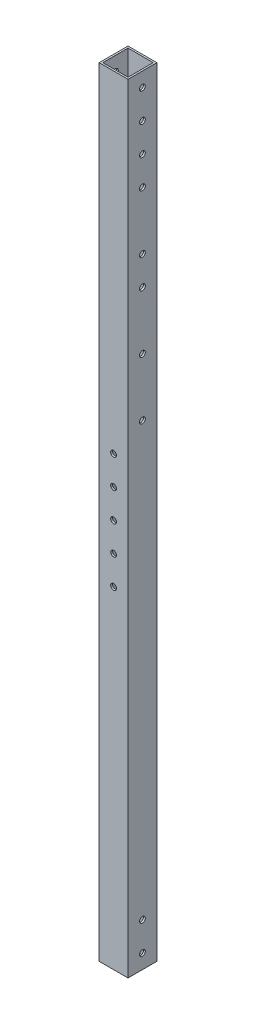
SolidWorks part; units mm, degrees
material "6061-T6 (SS)"
ref_plane "Front Plane" through (0, 0, 0) normal (0, 0, 1) x (1, 0, 0)
ref_plane "Top Plane" through (0, 0, 0) normal (0, 1, 0) x (1, 0, 0)
ref_plane "Right Plane" through (0, 0, 0) normal (1, 0, 0) x (0, 0, -1)
sketch "Sketch1" plane through (0, 0, 0) normal (0, 1, 0) x (1, 0, 0)
  line L1 (-12.7, -12.7) -> (12.7, -12.7)
  line L2 (-12.7, -12.7) -> (-12.7, 12.7)
  line L3 (-12.7, 12.7) -> (12.7, 12.7)
  line L4 (12.7, -12.7) -> (12.7, 12.7)
  line L5 (-12.7, -12.7) -> (12.7, 12.7) construction
  line L6 (-12.7, 12.7) -> (12.7, -12.7) construction
  line L7 (-11.1125, -11.1125) -> (11.1125, -11.1125)
  line L8 (-11.1125, -11.1125) -> (-11.1125, 11.1125)
  line L9 (-11.1125, 11.1125) -> (11.1125, 11.1125)
  line L10 (11.1125, -11.1125) -> (11.1125, 11.1125)
  line L11 (-11.1125, -11.1125) -> (11.1125, 11.1125) construction
  line L12 (-11.1125, 11.1125) -> (11.1125, -11.1125) construction
  point P0 (0, 0)
  point P6 (0, 0)
  dimension "D1" = 25.4
  dimension "D2" = 1.5875
extrude "Boss-Extrude1" add sketch "Sketch1" along normal blind 685.8
hole_wizard "#7 (0.201) Diameter Hole1" positions "Sketch2" profile "Sketch3" hole size "#7" standard "ANSI Inch"
sketch "Sketch2" plane through (0, 0, 12.7) normal (0, 0, 1) x (1, 0, 0)
  point P21 (0, 292.1)
  point P22 (0, 317.5)
  point P23 (0, 342.9)
  point P24 (0, 368.3)
  point P25 (0, 393.7)
  point P38 (0, 673.1)
  point P39 (0, 647.7)
  point P40 (0, 622.3)
  point P41 (0, 596.9)
  point P42 (0, 571.5)
  point P43 (0, 546.1)
  point P44 (0, 520.7)
  point P45 (0, 495.3)
  point P46 (0, 469.9)
  point P47 (0, 444.5)
  point P48 (0, 419.1)
  point P49 (0, 241.3)
  point P50 (0, 215.9)
  point P51 (0, 190.5)
  point P52 (0, 165.1)
  point P53 (0, 139.7)
  point P54 (0, 114.3)
  point P55 (0, 88.9)
  point P56 (0, 63.5)
  point P57 (0, 38.1)
  dimension "D1" = 292.1
  dimension "D3" = 25.4
  dimension "D2" = 25.4
  dimension "D4" = 25.4
  dimension "D5" = 25.4
sketch "Sketch3" plane through (0, 292.1, 12.7) normal (1, 0, 0) x (0, -1, 0)
  line L0 (0, 0) -> (0, 25.4)
  line L1 (0, 25.4) -> (2.5527, 25.4)
  line L2 (2.5527, 25.4) -> (2.5527, 0)
  line L5 (2.5527, 0) -> (0, 0)
  line L11 (0, -6.35) -> (0, 107.95) construction
  dimension "Thru Hole Dia." = 5.1054
  dimension "Thru Hole Depth" = 25.4
hole_wizard "#7 (0.201) Diameter Hole2" positions "Sketch4" profile "Sketch5" hole size "#7" standard "ANSI Inch"
sketch "Sketch4" plane through (12.7, 0, 0) normal (1, 0, 0) x (0, 0, -1)
  line L0 (-12.7, 0) -> (12.7, 0) construction
  point P0 (0, 12.7)
  point P12 (0, 38.1)
  point P35 (0, 622.3)
  point P36 (0, 647.7)
  point P37 (0, 673.1)
  point P39 (0, 596.9) [skipped]
  point P40 (0, 571.5) [skipped]
  point P41 (0, 546.1) [skipped]
  point P42 (0, 520.7) [skipped]
  point P43 (0, 495.3) [skipped]
  point P44 (0, 469.9) [skipped]
  point P45 (0, 444.5) [skipped]
  point P46 (0, 419.1) [skipped]
  point P47 (0, 393.7) [skipped]
  point P48 (0, 368.3) [skipped]
  point P49 (0, 342.9) [skipped]
  point P50 (0, 317.5) [skipped]
  point P51 (0, 292.1) [skipped]
  point P52 (0, 266.7) [skipped]
  point P53 (0, 241.3) [skipped]
  point P54 (0, 215.9) [skipped]
  point P55 (0, 190.5) [skipped]
  point P56 (0, 165.1) [skipped]
  point P57 (0, 139.7) [skipped]
  point P58 (0, 114.3) [skipped]
  point P59 (0, 88.9) [skipped]
  point P60 (0, 63.5) [skipped]
  point P61 (0, 596.9)
  point P63 (0, 520.7)
  point P66 (0, 546.1)
  point P70 (0, 469.9)
  point P74 (0, 419.1)
  dimension "D1" = 12.7
  dimension "D3" = 25.4
  dimension "D4" = 25.4
  dimension "D5" = 76.2
  dimension "D6" = 50.8
  dimension "D7" = 50.8
  dimension "D8" = 50.8
  dimension "D2" = 27
sketch "Sketch5" plane through (12.7, 12.7, 0) normal (0, 1, 0) x (0, 0, -1)
  line L0 (0, 0) -> (0, 25.4)
  line L1 (0, 25.4) -> (2.5527, 25.4)
  line L2 (2.5527, 25.4) -> (2.5527, 0)
  line L5 (2.5527, 0) -> (0, 0)
  line L11 (0, -6.35) -> (0, 107.95) construction
  dimension "Thru Hole Dia." = 5.1054
  dimension "Thru Hole Depth" = 25.4
